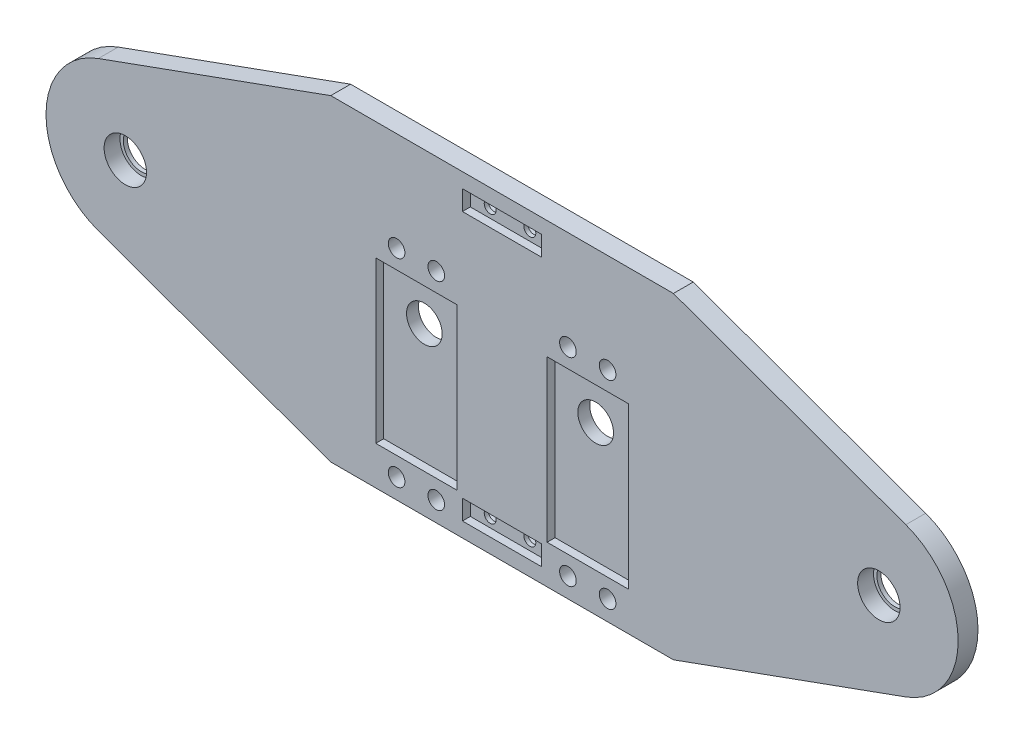
SolidWorks part; units mm, degrees
ref_plane "前视基准面" through (0, 0, 0) normal (0, 0, 1) x (1, 0, 0)
ref_plane "上视基准面" through (0, 0, 0) normal (0, 1, 0) x (1, 0, 0)
ref_plane "右视基准面" through (0, 0, 0) normal (1, 0, 0) x (0, 0, -1)
other "Configuration Table"
sketch "草图1" plane through (0, 0, 0) normal (0, 0, 1) x (1, 0, 0)
  line L0 (0, 0) -> (95, 0)
  line L1 (95, 0) -> (73.4, 0)
  line L2 (95, 0) -> (73.4, 0)
  line L3 (73.4, 0) -> (51.8, 0)
  line L4 (51.8, 0) -> (51.8, 40)
  line L5 (51.8, 0) -> (51.8, -40)
  line L6 (51.8, -40) -> (138.2, -40)
  line L7 (95, -40) -> (95, 0)
  line L8 (51.8, 40) -> (138.2, 40)
  line L9 (95, 40) -> (95, 0)
  line L10 (51.8, 40) -> (-6.8015, 18.808)
  line L11 (51.8, -40) -> (-6.8015, -18.808)
  line L12 (138.2, -40) -> (196.8015, -18.808)
  line L13 (138.2, 40) -> (196.8015, 18.808)
  circle A0 centre (0, 0) radius 4.5
  circle A1 centre (0, 0) radius 20
  circle A2 centre (73.4, 0) radius 4.5
  circle A3 centre (116.6, 0) radius 4.5
  circle A4 centre (190, 0) radius 20
  circle A5 centre (190, 0) radius 4.5
  dimension "D1" = 9
  dimension "D3" = 40
  dimension "D5" = 9
  dimension "D9" = 9
  dimension "D2" = 95
  dimension "D4" = 21.6
  dimension "D6" = 21.6
  dimension "D7" = 40
  dimension "D8" = 40
extrude "凸台-拉伸4" add sketch "草图1" along normal blind 5
sketch "草图3" plane through (0, 0, 5) normal (0, 0, 1) x (1, 0, 0)
  circle A0 centre (0, 0) radius 5.35
  circle A1 centre (190, 0) radius 5.35
  dimension "D1" = 10.7
  dimension "D2" = 10.7
extrude "切除-拉伸3" cut sketch "草图3" against normal blind 4
sketch "草图4" plane through (0, 0, 5) normal (0, 0, 1) x (1, 0, 0)
  line L0 (95, -960) -> (95, 49040) construction
  line L1 (-905, 33.9574) -> (49095, 33.9574) construction
  line L3 (51.8, 40) -> (138.2, 40) construction
  line L6 (75, 28.9574) -> (75, 38.9574)
  line L7 (75, 38.9574) -> (115, 38.9574)
  line L8 (115, 28.9574) -> (115, 38.9574)
  line L9 (75, 28.9574) -> (115, 38.9574) construction
  line L10 (75, 38.9574) -> (115, 28.9574) construction
  circle A0 centre (95, 33.9574) radius 1.5
  circle A1 centre (85, 33.9574) radius 1.6
  circle A2 centre (105, 33.9574) radius 1.6
  point P5 (95, 40)
  point P15 (0, 0)
  dimension "D1" = 3
  dimension "D4" = 3.2
  dimension "D2" = 40
  dimension "D3" = 10
  dimension "D5" = 10
sketch "草图11" plane through (0, 0, 5) normal (0, 0, 1) x (1, 0, 0)
  line L0 (95, 40) -> (95, -40)
  line L1 (51.8, 40) -> (138.2, 40) construction
  line L2 (51.8, -40) -> (138.2, -40) construction
  line L3 (95, 33.7901) -> (100, 33.7901)
  line L4 (-905, 0) -> (49095, 0) construction
  circle A0 centre (95, 33.7901) radius 1.6
  circle A1 centre (100, 33.7901) radius 1.5
  circle A2 centre (90, 33.7901) radius 1.5
  circle A3 centre (100, -33.7901) radius 1.5
  circle A4 centre (90, -33.7901) radius 1.5
  point P15 (95, 0)
  dimension "D1" = 3.2
  dimension "D3" = 3
  dimension "D2" = 5
extrude "切除-拉伸13" cut sketch "草图11" against normal through all contours A2 | A1 | A4 | A3
sketch "草图12" plane through (0, 0, 5) normal (0, 0, 1) x (1, 0, 0)
  line L0 (90, 33.7901) -> (100, 33.7901)
  line L1 (-1000, 0) -> (49000, 0) construction
  line L2 (85, 36.2901) -> (105, 36.2901)
  line L3 (85, 36.2901) -> (85, 31.2901)
  line L4 (85, 31.2901) -> (105, 31.2901)
  line L5 (105, 36.2901) -> (105, 31.2901)
  line L6 (85, 36.2901) -> (105, 31.2901) construction
  line L7 (85, 31.2901) -> (105, 36.2901) construction
  line L8 (85, -31.2901) -> (105, -36.2901) construction
  line L9 (85, -36.2901) -> (105, -31.2901) construction
  line L10 (105, -36.2901) -> (105, -31.2901)
  line L11 (85, -31.2901) -> (105, -31.2901)
  line L12 (85, -36.2901) -> (85, -31.2901)
  line L13 (85, -36.2901) -> (105, -36.2901)
  line L14 (90, -33.7901) -> (100, -33.7901)
  point P4 (95, 33.7901)
  point P18 (95, -33.7901)
  dimension "D1" = 20
  dimension "D2" = 5
extrude "切除-拉伸14" cut sketch "草图12" against normal blind 2
sketch "草图13" plane through (0, 0, 0) normal (0, 0, -1) x (-1, 0, 0)
  line L1 (-105, 36.2901) -> (-85, 36.2901)
  line L2 (-105, 36.2901) -> (-105, 31.2901)
  line L3 (-105, 31.2901) -> (-85, 31.2901)
  line L4 (-85, 36.2901) -> (-85, 31.2901)
  line L5 (-105, -31.2901) -> (-85, -31.2901)
  line L6 (-105, -31.2901) -> (-105, -36.2901)
  line L7 (-105, -36.2901) -> (-85, -36.2901)
  line L8 (-85, -31.2901) -> (-85, -36.2901)
extrude "切除-拉伸15" cut sketch "草图13" against normal blind 2
sketch "草图14" plane through (0, 0, 5) normal (0, 0, 1) x (1, 0, 0)
  line L0 (73.4, 0) -> (73.4, -35)
  line L1 (73.4, -35) -> (78.4, -35)
  line L2 (95, -966.2099) -> (95, 49033.7901) construction
  line L3 (73.4, 0) -> (73.4, 15)
  line L4 (73.4, 15) -> (78.4, 15)
  circle A0 centre (78.4, -35) radius 2.1
  circle A1 centre (68.4, -35) radius 2.1
  circle A2 centre (111.6, -35) radius 2.1
  circle A3 centre (121.6, -35) radius 2.1
  circle A4 centre (78.4, 15) radius 2.1
  circle A5 centre (68.4, 15) radius 2.1
  circle A6 centre (111.6, 15) radius 2.1
  circle A7 centre (121.6, 15) radius 2.1
  dimension "D3" = 4.2
  dimension "D6" = 4.2
  dimension "D1" = 35
  dimension "D2" = 5
  dimension "D4" = 15
  dimension "D5" = 5
extrude "切除-拉伸17" cut sketch "草图14" against normal through all
sketch "草图15" plane through (0, 0, 5) normal (0, 0, 1) x (1, 0, 0)
  line L0 (68.4, 15) -> (68.4, -35) construction
  line L1 (68.4, -35) -> (78.4, -35) construction
  line L2 (-931.6, -10) -> (49068.4, -10) construction
  line L3 (73.4, -1035) -> (73.4, 48965) construction
  line L4 (95, -963.7099) -> (95, 49036.2901) construction
  line L5 (63.15, -30.25) -> (83.65, -30.25)
  line L6 (63.15, -30.25) -> (63.15, 10.25)
  line L7 (63.15, 10.25) -> (83.65, 10.25)
  line L8 (83.65, -30.25) -> (83.65, 10.25)
  line L9 (63.15, -30.25) -> (83.65, 10.25) construction
  line L10 (63.15, 10.25) -> (83.65, -30.25) construction
  line L11 (85, 36.2901) -> (105, 36.2901) construction
  line L12 (126.85, -30.25) -> (106.35, -30.25)
  line L13 (106.35, -30.25) -> (106.35, 10.25)
  line L14 (126.85, -30.25) -> (126.85, 10.25)
  line L15 (126.85, 10.25) -> (106.35, 10.25)
  point P9 (68.4, -10)
  point P10 (73.4, -10)
  point P12 (73.4, -35)
  point P22 (95, 36.2901)
  dimension "D1" = 20.5
  dimension "D2" = 40.5
extrude "切除-拉伸18" cut sketch "草图15" against normal blind 2
